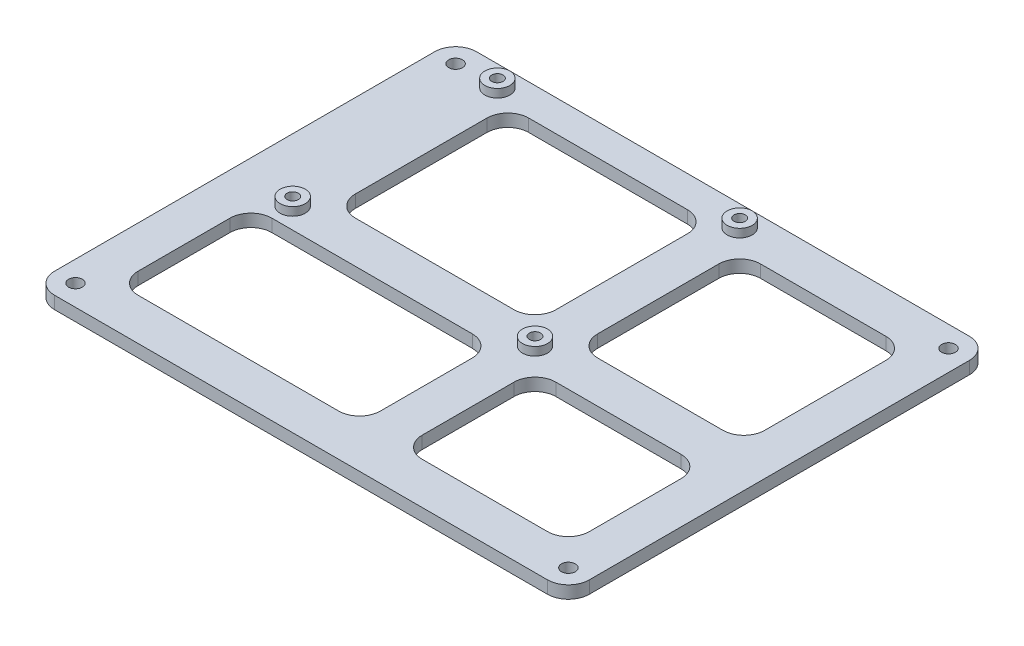
SolidWorks part; units mm, degrees
ref_plane "Front Plane" through (0, 0, 0) normal (0, 0, 1) x (1, 0, 0)
ref_plane "Top Plane" through (0, 0, 0) normal (0, 1, 0) x (1, 0, 0)
ref_plane "Right Plane" through (0, 0, 0) normal (1, 0, 0) x (0, 0, -1)
sketch "Sketch1" plane through (0, 0, 0) normal (0, 1, 0) x (1, 0, 0)
  line L0 (52, 45.5) -> (52, -45.5) construction
  line L1 (-66, -45.5) -> (66, -45.5) construction
  line L2 (-66, -45.5) -> (-66, 45.5) construction
  line L3 (-66, 45.5) -> (66, 45.5) construction
  line L4 (66, -45.5) -> (66, 45.5) construction
  line L5 (-66, -45.5) -> (66, 45.5) construction
  line L6 (-66, 45.5) -> (66, -45.5) construction
  circle A0 centre (-66, 45.5) radius 1.65
  circle A1 centre (-66, -45.5) radius 1.65
  circle A2 centre (66, -45.5) radius 1.65
  circle A3 centre (66, 45.5) radius 1.65
  circle A4 centre (52, 45.5) radius 1.65
  circle A5 centre (52, -45.5) radius 1.65
  point P0 (0, 0)
  point P16 (0, 0)
  point P17 (43.6053, 45.5)
  point P18 (39.0001, -45.5)
  dimension "D3" = 3.3
  dimension "D4" = 3.3
  dimension "D5" = 3.3
  dimension "D6" = 3.3
  dimension "D7" = 14
  dimension "D1" = 132
  dimension "D2" = 91
sketch "Sketch2" plane through (0, 0, 0) normal (0, 1, 0) x (1, 0, 0)
  line L0 (-66, 45.5) -> (66, 45.5) construction
  line L1 (2, 45.5) -> (-56, 45.5) construction
  line L2 (2, 45.5) -> (2, -3.5) construction
  line L3 (2, -3.5) -> (-56, -3.5) construction
  line L4 (-56, 45.5) -> (-56, -3.5) construction
  line L5 (2, 45.5) -> (-56, -3.5) construction
  line L6 (2, -3.5) -> (-56, 45.5) construction
  line L7 (-66, -45.5) -> (-66, 45.5) construction
  line L8 (-66, -45.5) -> (66, -45.5) construction
  line L9 (-66, 50.5) -> (52, 50.5)
  line L10 (-71, 45.5) -> (-71, -45.5)
  line L11 (-66, -50.5) -> (52, -50.5)
  line L12 (57, 45.5) -> (57, -45.5)
  line L13 (52, 45.5) -> (52, -45.5) construction
  line L15 (12, 40.5) -> (42, 40.5)
  line L16 (7, 35.5) -> (7, 6.5)
  line L17 (12, 1.5) -> (42, 1.5)
  line L18 (47, 35.5) -> (47, 6.5)
  line L19 (12, -8.5) -> (42, -8.5)
  line L20 (7, -13.5) -> (7, -35.5)
  line L21 (12, -40.5) -> (42, -40.5)
  line L22 (47, -13.5) -> (47, -35.5)
  line L23 (-8, -8.5) -> (-56, -8.5)
  line L24 (-3, -13.5) -> (-3, -35.5)
  line L25 (-8, -40.5) -> (-56, -40.5)
  line L26 (-61, -13.5) -> (-61, -35.5)
  line L27 (-46, 43) -> (-8, 43)
  line L28 (-51, 38) -> (-51, 6.5)
  line L29 (-46, 1.5) -> (-8, 1.5)
  line L30 (-3, 38) -> (-3, 6.5)
  circle A0 centre (52, 45.5) radius 1.65 construction
  circle A1 centre (52, -45.5) radius 1.65 construction
  circle A2 centre (-66, -45.5) radius 1.65 construction
  circle A3 centre (-66, 45.5) radius 1.65 construction
  circle A4 centre (52, 45.5) radius 1.65
  circle A5 centre (52, -45.5) radius 1.65
  circle A6 centre (-66, -45.5) radius 1.65
  circle A7 centre (-66, 45.5) radius 1.65
  circle A8 centre (-56, -3.5) radius 1.35
  circle A9 centre (-56, 45.5) radius 1.35
  circle A10 centre (2, 45.5) radius 1.35
  circle A11 centre (2, -3.5) radius 1.35
  arc A12 (-66, 50.5) -> (-71, 45.5) centre (-66, 45.5) ccw
  arc A13 (52, 50.5) -> (57, 45.5) centre (52, 45.5) cw
  arc A14 (52, -50.5) -> (57, -45.5) centre (52, -45.5) ccw
  arc A15 (-71, -45.5) -> (-66, -50.5) centre (-66, -45.5) ccw
  arc A16 (-8, 43) -> (-3, 38) centre (-8, 38) cw
  arc A17 (-46, 43) -> (-51, 38) centre (-46, 38) ccw
  arc A18 (-51, 6.5) -> (-46, 1.5) centre (-46, 6.5) ccw
  arc A19 (-8, 1.5) -> (-3, 6.5) centre (-8, 6.5) ccw
  arc A20 (7, 6.5) -> (12, 1.5) centre (12, 6.5) ccw
  arc A21 (12, 40.5) -> (7, 35.5) centre (12, 35.5) ccw
  arc A22 (42, 40.5) -> (47, 35.5) centre (42, 35.5) cw
  arc A23 (42, 1.5) -> (47, 6.5) centre (42, 6.5) ccw
  arc A24 (42, -8.5) -> (47, -13.5) centre (42, -13.5) cw
  arc A25 (42, -40.5) -> (47, -35.5) centre (42, -35.5) ccw
  arc A26 (7, -35.5) -> (12, -40.5) centre (12, -35.5) ccw
  arc A27 (12, -8.5) -> (7, -13.5) centre (12, -13.5) ccw
  arc A28 (-8, -8.5) -> (-3, -13.5) centre (-8, -13.5) cw
  arc A29 (-3, -35.5) -> (-8, -40.5) centre (-8, -35.5) cw
  arc A30 (-56, -40.5) -> (-61, -35.5) centre (-56, -35.5) cw
  arc A31 (-56, -8.5) -> (-61, -13.5) centre (-56, -13.5) ccw
  point P12 (-27, 21)
  dimension "D3" = 2.7
  dimension "D9" = 5
  dimension "D22" = 5
  dimension "D1" = 58
  dimension "D2" = 49
  dimension "D4" = 10
  dimension "D5" = 5
  dimension "D6" = 5
  dimension "D7" = 5
  dimension "D8" = 5
  dimension "D10" = 5
  dimension "D11" = 5
  dimension "D12" = 5
  dimension "D13" = 5
  dimension "D14" = 5
  dimension "D15" = 10
  dimension "D16" = 5
  dimension "D17" = 5
  dimension "D18" = 5
  dimension "D19" = 5
  dimension "D20" = 5
  dimension "D21" = 5
extrude "Boss-Extrude1" add sketch "Sketch2" along normal blind 3
sketch "Sketch3" plane through (0, 3, 0) normal (0, 1, 0) x (1, 0, 0)
  circle A0 centre (-56, 45.5) radius 1.35 construction
  circle A1 centre (2, 45.5) radius 1.35 construction
  circle A2 centre (2, -3.5) radius 1.35 construction
  circle A3 centre (-56, -3.5) radius 1.35 construction
  circle A4 centre (-56, 45.5) radius 1.35
  circle A5 centre (2, 45.5) radius 1.35
  circle A6 centre (2, -3.5) radius 1.35
  circle A7 centre (-56, -3.5) radius 1.35
  circle A8 centre (-56, -3.5) radius 3
  circle A9 centre (2, -3.5) radius 3
  circle A10 centre (2, 45.5) radius 3
  circle A11 centre (-56, 45.5) radius 3
  dimension "D1" = 6
extrude "Boss-Extrude2" add sketch "Sketch3" along normal blind 2
equation "\"D11@Sketch2\"=\"D5@Sketch2\""
equation "\"D12@Sketch2\"=\"D11@Sketch2\""
equation "\"D13@Sketch2\"=\"D10@Sketch2\""
equation "\"D14@Sketch2\"=\"D13@Sketch2\""
equation "\"D16@Sketch2\"=5"
equation "\"D17@Sketch2\"=5"
